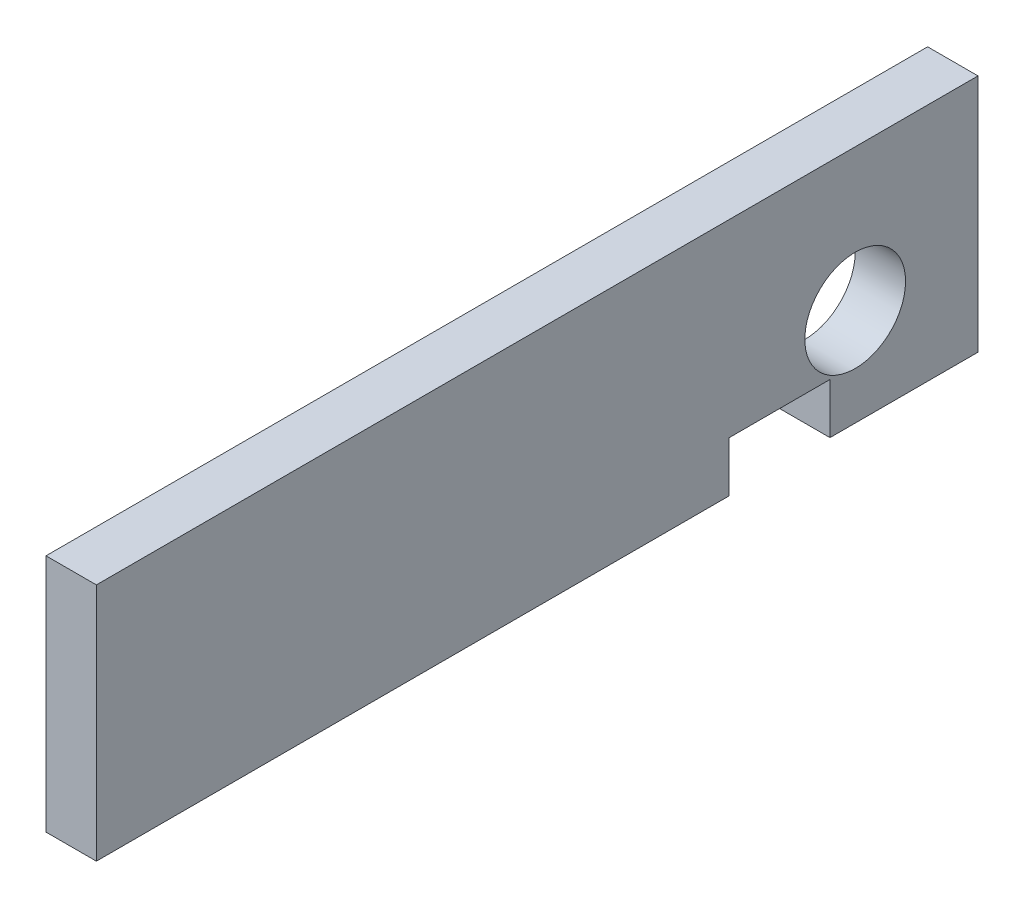
SolidWorks part; units mm, degrees
ref_plane "front" through (0, 0, 0) normal (0, 0, 1) x (1, 0, 0)
ref_plane "top" through (0, 0, 0) normal (0, 1, 0) x (1, 0, 0)
ref_plane "right" through (0, 0, 0) normal (1, 0, 0) x (0, 0, -1)
sketch "Sketch1" plane through (0, 0, 0) normal (0, 0, 1) x (1, 0, 0)
  line L1 (-12.7, 120.65) -> (12.7, 120.65)
  line L2 (-12.7, 120.65) -> (-12.7, 0)
  line L3 (-12.7, 0) -> (12.7, 0)
  line L4 (12.7, 120.65) -> (12.7, 0)
  dimension "D1" = 25.4
  dimension "D2" = 120.65
extrude "Extrude1" add sketch "Sketch1" against normal blind 444.5
sketch "Sketch2" plane through (0, 0, 0) normal (1, 0, 0) x (0, 0, -1)
  line L1 (444.5, 0) -> (444.5, 120.65) construction
  line L2 (444.5, 0) -> (0, 0) construction
  circle A0 centre (382.5748, 49.2252) radius 25.4
  dimension "D5" = 50.8
  dimension "D1" = 61.9252
  dimension "D2" = 49.2252
extrude "Cut-Extrude1" cut sketch "Sketch2" against normal mid plane 50.8
ref_plane "Plane1" through (0, 0, -369.8748) normal (0, 0, -1) x (-1, 0, 0)
sketch "Sketch4" plane through (0, 0, -369.8748) normal (0, 0, -1) x (-1, 0, 0)
  line L0 (-22.2076, 34.9076) -> (28.7311, -16.0311)
  line L1 (28.7311, -16.0311) -> (-22.2076, -16.0311)
  line L2 (-22.2076, -16.0311) -> (-22.2076, 34.9076)
  line L5 (12.7, 0) -> (-12.7, 0) construction
  line L6 (-12.7, 0) -> (-12.7, 120.65) construction
  point P2 (12.7, 0)
  dimension "D1" = 45
  dimension "D2" = 25.4
extrude "Cut-Extrude2" cut sketch "Sketch4" against normal blind 50.8
